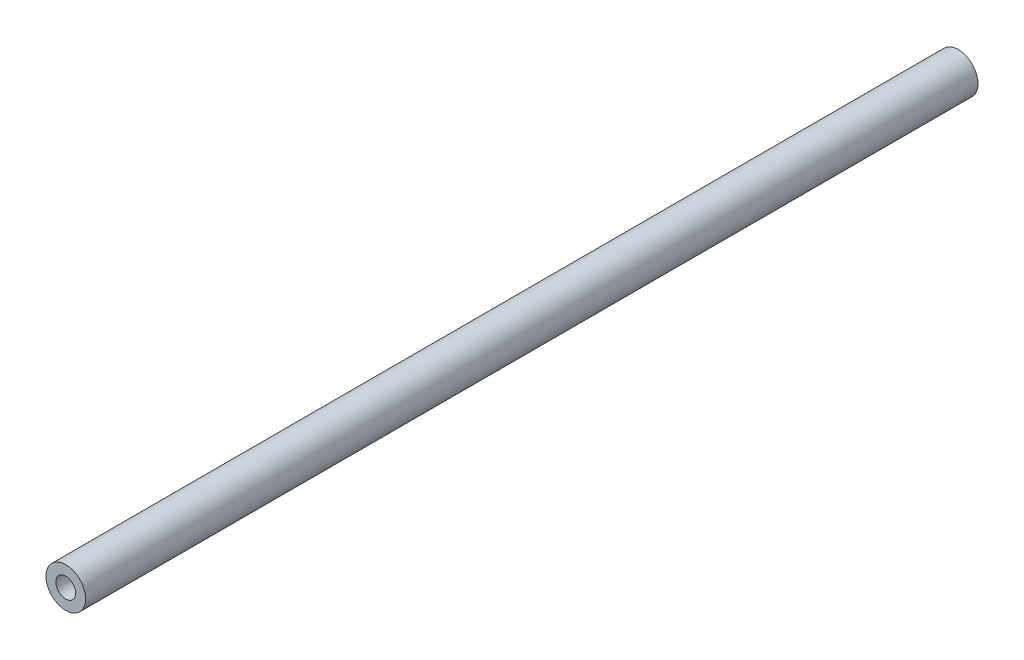
SolidWorks part; units mm, degrees
ref_plane "정면" through (0, 0, 0) normal (0, 0, 1) x (1, 0, 0)
ref_plane "윗면" through (0, 0, 0) normal (0, 1, 0) x (1, 0, 0)
ref_plane "우측면" through (0, 0, 0) normal (1, 0, 0) x (0, 0, -1)
sketch "스케치2" plane through (0, 0, 0) normal (0, 0, 1) x (1, 0, 0)
  circle A0 centre (0, 0) radius 10
  circle A1 centre (0, 0) radius 5
  dimension "D1" = 20
  dimension "D2" = 10
extrude "보스-돌출1" add sketch "스케치2" along normal blind 450
